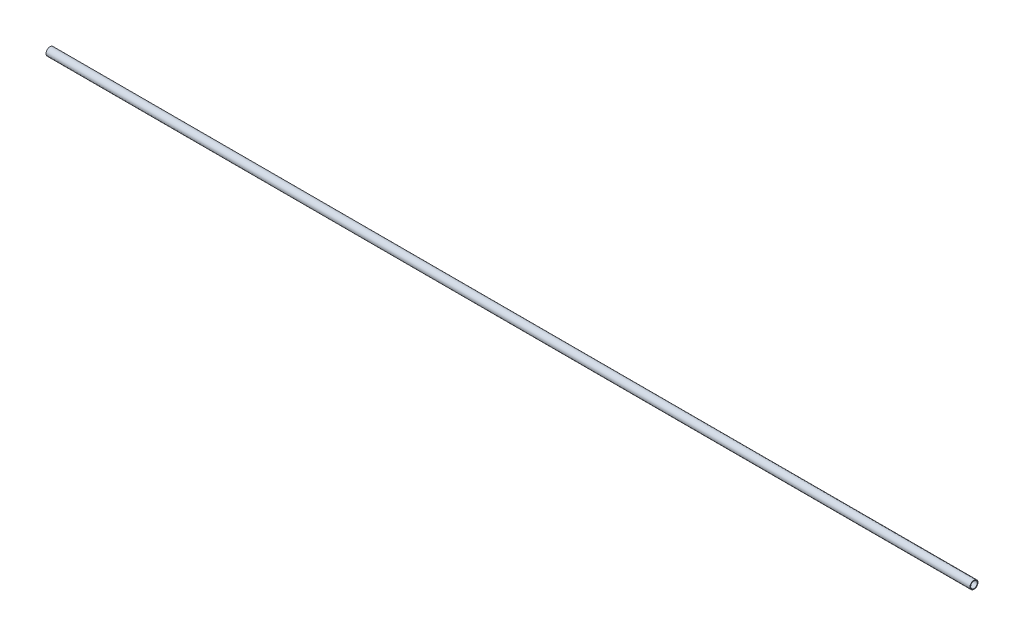
SolidWorks part; units mm, degrees
ref_plane "Front" through (0, 0, 0) normal (0, 0, 1) x (1, 0, 0)
ref_plane "Top" through (0, 0, 0) normal (0, 1, 0) x (1, 0, 0)
ref_plane "Right" through (0, 0, 0) normal (1, 0, 0) x (0, 0, -1)
sketch "Sketch1" plane through (0, 0, 0) normal (1, 0, 0) x (0, 0, -1)
  circle A0 centre (0, 0) radius 3.9688
  circle A1 centre (0, 0) radius 3.2639
  point P4 (3.9688, 0)
  point P5 (3.2639, 0)
  dimension "OD" = 7.9375
  dimension "ID" = 6.5278
  dimension "Wall" = 0.7048
extrude "Extrude1" add sketch "Sketch1" along normal mid plane 914.4
